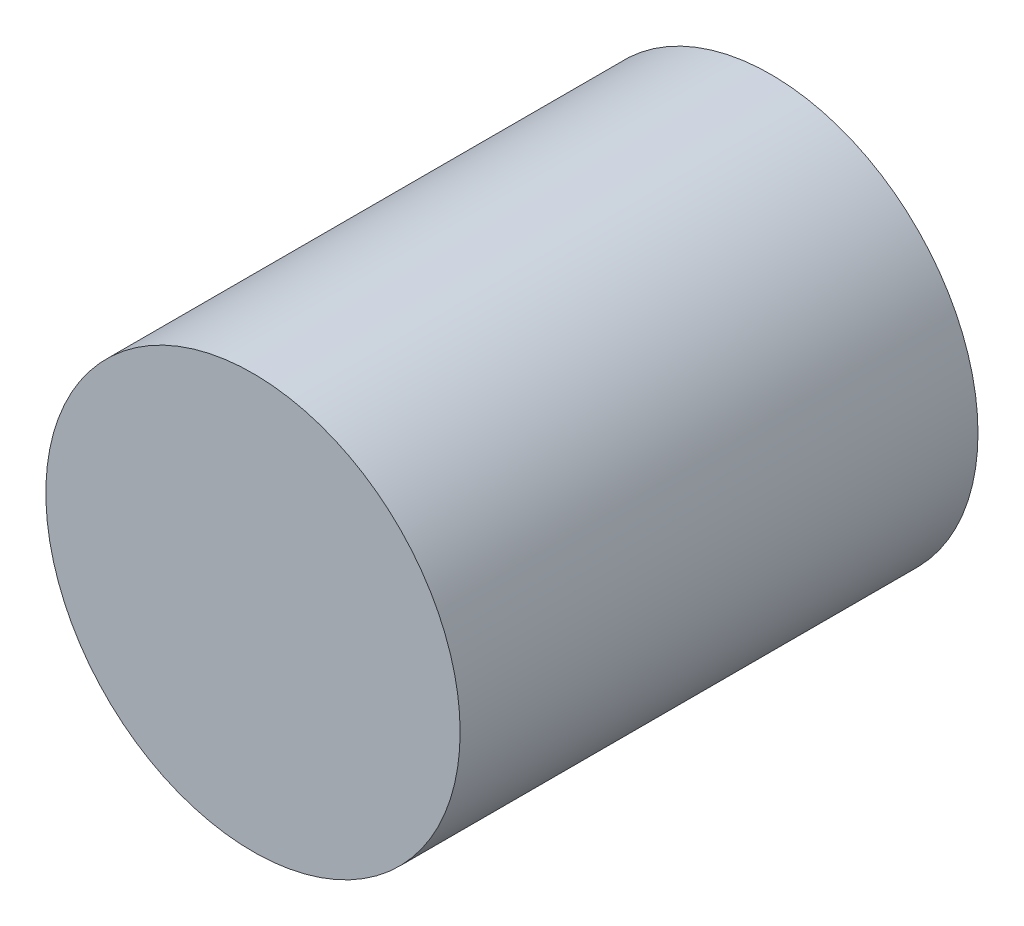
SolidWorks part; units mm, degrees
ref_plane "Спереди" through (0, 0, 0) normal (0, 0, 1) x (1, 0, 0)
ref_plane "Сверху" through (0, 0, 0) normal (0, 1, 0) x (1, 0, 0)
ref_plane "Справа" through (0, 0, 0) normal (1, 0, 0) x (0, 0, -1)
sketch "Эскиз1" plane through (0, 0, 0) normal (0, 0, 1) x (1, 0, 0)
  circle A0 centre (0, 0) radius 20
  dimension "D1" = 40
extrude "Бобышка-Вытянуть1" add sketch "Эскиз1" along normal blind 50
